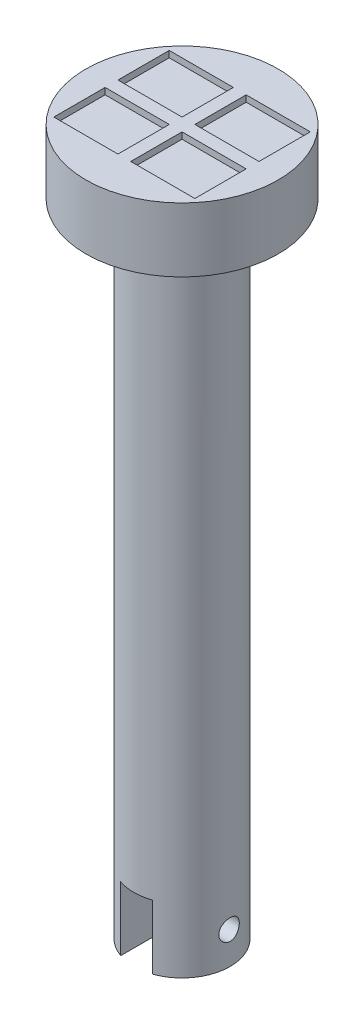
SolidWorks part; units mm, degrees
ref_plane "正面" through (0, 0, 0) normal (0, 0, 1) x (1, 0, 0)
ref_plane "平面" through (0, 0, 0) normal (0, 1, 0) x (1, 0, 0)
ref_plane "右側面" through (0, 0, 0) normal (1, 0, 0) x (0, 0, -1)
sketch "ｽｹｯﾁ1" plane through (0, 0, 0) normal (0, 1, 0) x (1, 0, 0)
  circle A0 centre (0, 0) radius 7.5
  dimension "D1" = 15
extrude "ﾎﾞｽ - 押し出し1" add sketch "ｽｹｯﾁ1" along normal blind 100 contours A0
sketch "ｽｹｯﾁ2" plane through (0, 100, 0) normal (0, 1, 0) x (1, 0, 0)
  circle A0 centre (0, 0) radius 15
  dimension "D1" = 30
extrude "ﾎﾞｽ - 押し出し2" add sketch "ｽｹｯﾁ2" along normal blind 10
sketch "ｽｹｯﾁ3" plane through (0, 0, 0) normal (0, 0, 1) x (1, 0, 0)
  line L0 (-7.5, 0) -> (7.5, 0) construction
  line L1 (-2.5, 0) -> (2.5, 0)
  line L2 (-2.5, 0) -> (-2.5, 10)
  line L3 (-2.5, 10) -> (2.5, 10)
  line L4 (2.5, 0) -> (2.5, 10)
  point P6 (0, 0)
  dimension "D1" = 5
  dimension "D2" = 10
extrude "ｶｯﾄ - 押し出し1" cut sketch "ｽｹｯﾁ3" against normal through all and the other way through all
sketch "ｽｹｯﾁ4" plane through (0, 0, 0) normal (1, 0, 0) x (0, 0, -1)
  line L0 (7.0711, 10) -> (7.5, 10) construction
  circle A0 centre (0, 5) radius 1.6
  dimension "D1" = 3.2
  dimension "D2" = 5
extrude "ｶｯﾄ - 押し出し2" cut sketch "ｽｹｯﾁ4" against normal through all and the other way through all
sketch "ｽｹｯﾁ5" plane through (0, 110, 0) normal (0, 1, 0) x (1, 0, 0)
  line L0 (0, 13.7491) -> (0, -11.8067) construction
  line L1 (-11, 9) -> (-1, 9)
  line L2 (-11, 9) -> (-11, 1)
  line L3 (-11, 1) -> (-1, 1)
  line L4 (-1, 9) -> (-1, 1)
  line L5 (-12.9493, 0) -> (13.0636, 0) construction
  line L6 (11, 1) -> (1, 1)
  line L7 (1, 9) -> (1, 1)
  line L8 (11, 9) -> (1, 9)
  line L9 (11, 9) -> (11, 1)
  line L10 (11, -9) -> (11, -1)
  line L11 (11, -9) -> (1, -9)
  line L12 (1, -9) -> (1, -1)
  line L13 (11, -1) -> (1, -1)
  line L14 (-11, -1) -> (-1, -1)
  line L15 (-1, -9) -> (-1, -1)
  line L16 (-11, -9) -> (-1, -9)
  line L17 (-11, -9) -> (-11, -1)
  dimension "D1" = 10
  dimension "D2" = 8
  dimension "D3" = 1
  dimension "D4" = 1
extrude "ｶｯﾄ - 押し出し3" cut sketch "ｽｹｯﾁ5" against normal blind 1
